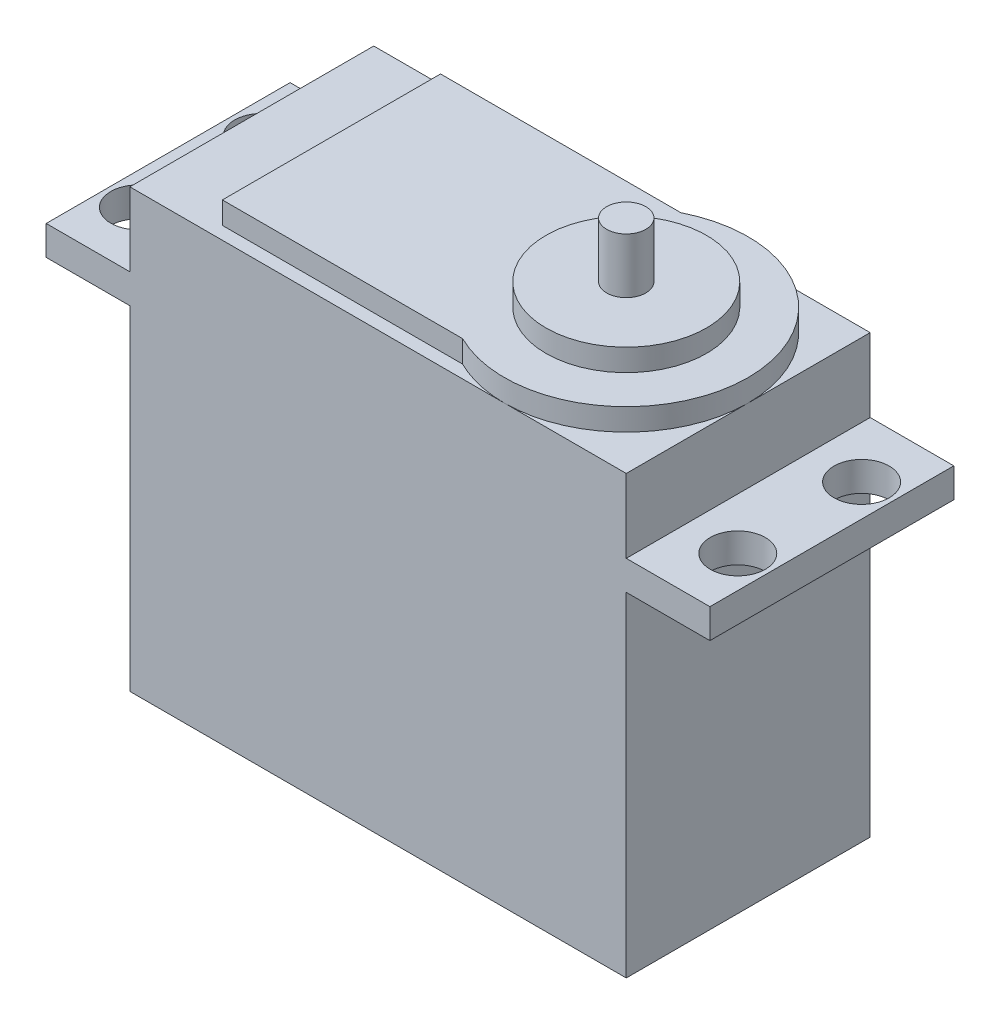
SolidWorks part; units mm, degrees
ref_plane "前视基准面" through (0, 0, 0) normal (0, 0, 1) x (1, 0, 0)
ref_plane "上视基准面" through (0, 0, 0) normal (0, 1, 0) x (1, 0, 0)
ref_plane "右视基准面" through (0, 0, 0) normal (1, 0, 0) x (0, 0, -1)
sketch "草图1" plane through (0, 0, 0) normal (0, 1, 0) x (1, 0, 0)
  line L1 (-20.25, -9.95) -> (20.25, -9.95)
  line L2 (-20.25, -9.95) -> (-20.25, 9.95)
  line L3 (-20.25, 9.95) -> (20.25, 9.95)
  line L4 (20.25, -9.95) -> (20.25, 9.95)
  line L5 (-20.25, -9.95) -> (20.25, 9.95) construction
  line L6 (-20.25, 9.95) -> (20.25, -9.95) construction
  point P0 (0, 0)
  dimension "D1" = 40.5
  dimension "D2" = 19.9
extrude "凸台-拉伸1" add sketch "草图1" along normal blind 28.25
sketch "草图2" plane through (0, 28.25, 0) normal (0, 1, 0) x (1, 0, 0)
  line L0 (20.25, 9.95) -> (-20.25, 9.95) construction
  line L1 (-27.075, -9.95) -> (27.075, -9.95)
  line L2 (-27.075, -9.95) -> (-27.075, 9.95)
  line L3 (-27.075, 9.95) -> (27.075, 9.95)
  line L4 (27.075, -9.95) -> (27.075, 9.95)
  line L5 (-27.075, -9.95) -> (27.075, 9.95) construction
  line L6 (-27.075, 9.95) -> (27.075, -9.95) construction
  point P0 (0, 0)
  dimension "D1" = 54.15
extrude "凸台-拉伸2" add sketch "草图2" along normal blind 2.4
sketch "草图3" plane through (0, 30.65, 0) normal (0, 1, 0) x (1, 0, 0)
  line L0 (20.25, -9.95) -> (20.25, 9.95) construction
  line L1 (-27.075, -9.95) -> (27.075, -9.95) construction
  line L2 (27.075, 9.95) -> (-27.075, 9.95) construction
  line L3 (-20.25, 9.95) -> (-20.25, -9.95) construction
  line L4 (20.25, -9.95) -> (20.25, 9.95)
  line L5 (-27.075, -9.95) -> (27.075, -9.95)
  line L6 (27.075, 9.95) -> (-27.075, 9.95)
  line L7 (-20.25, 9.95) -> (-20.25, -9.95)
  line M2 (27.075, 9.95) -> (-27.075, 9.95)
extrude "凸台-拉伸3" add sketch "草图3" along normal blind 6 separate body contours L7 L5 L4 M2
sketch "草图4" plane through (0, 36.65, 0) normal (0, 1, 0) x (1, 0, 0)
  line L0 (20.25, -9.95) -> (20.25, 9.95) construction
  line L2 (0, 0) -> (10.3, 0) construction
  line L3 (20.25, 9.95) -> (-20.25, 9.95) construction
  line L5 (-13.75, 8.9) -> (5.8511, 8.9)
  line L6 (-13.75, 8.9) -> (-13.75, -8.9)
  line L7 (-13.75, -8.9) -> (5.8511, -8.9)
  line L8 (5.8511, 8.9) -> (5.8511, -8.9)
  circle A0 centre (10.3, 0) radius 9.95
  dimension "D1" = 34
  dimension "D2" = 17.8
extrude "凸台-拉伸4" add sketch "草图4" along normal blind 1.8
sketch "草图5" plane through (0, 38.45, 0) normal (0, 1, 0) x (1, 0, 0)
  circle A0 centre (10.3, 0) radius 6.55
  arc A1 (5.8511, -8.9) -> (5.8511, 8.9) centre (10.3, 0) ccw construction
  dimension "D1" = 13.1
extrude "凸台-拉伸5" add sketch "草图5" along normal blind 1.8
sketch "草图6" plane through (0, 40.25, 0) normal (0, 1, 0) x (1, 0, 0)
  circle A0 centre (10.3, 0) radius 1.6
  circle A1 centre (10.3, 0) radius 6.55 construction
  dimension "D1" = 3.2
extrude "凸台-拉伸6" add sketch "草图6" along normal blind 4.5
sketch "草图7" plane through (0, 30.65, 0) normal (0, 1, 0) x (1, 0, 0)
  line L1 (-24.45, -5.05) -> (24.45, -5.05) construction
  line L2 (-24.45, -5.05) -> (-24.45, 5.05) construction
  line L3 (-24.45, 5.05) -> (24.45, 5.05) construction
  line L4 (24.45, -5.05) -> (24.45, 5.05) construction
  line L5 (-24.45, -5.05) -> (24.45, 5.05) construction
  line L6 (-24.45, 5.05) -> (24.45, -5.05) construction
  circle A0 centre (24.45, -5.05) radius 2.25
  circle A1 centre (24.45, 5.05) radius 2.25
  circle A2 centre (-24.45, 5.05) radius 2.25
  circle A3 centre (-24.45, -5.05) radius 2.25
  point P0 (0, 0)
  dimension "D1" = 4.5
  dimension "D2" = 10.1
  dimension "D3" = 48.9
extrude "切除-拉伸1" cut sketch "草图7" against normal through all
chamfer "倒角1" distance 1 angle 45 4 edges at (0, 0, -9.95) (-20.25, 0, 0) (0, 0, 9.95) (20.25, 0, 0)
